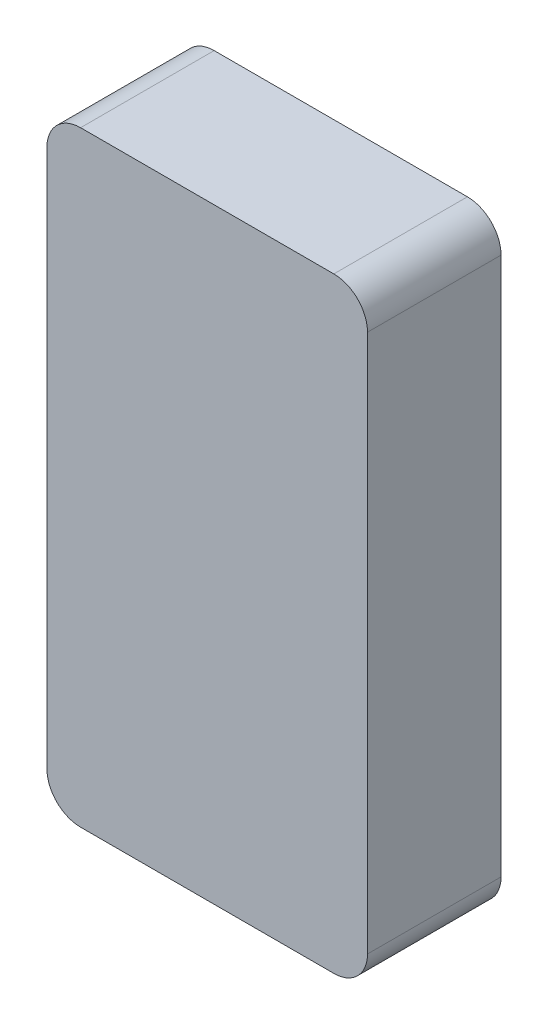
SolidWorks part; units mm, degrees
ref_plane "前基準面" through (0, 0, 0) normal (0, 0, 1) x (1, 0, 0)
ref_plane "上基準面" through (0, 0, 0) normal (0, 1, 0) x (1, 0, 0)
ref_plane "右基準面" through (0, 0, 0) normal (1, 0, 0) x (0, 0, -1)
sketch "Sketch1" plane through (0, 0, 0) normal (0, 0, 1) x (1, 0, 0)
  line L1 (0, 0) -> (4.7625, 0)
  line L2 (0, 0) -> (0, 9)
  line L3 (0, 9) -> (4.7625, 9)
  line L4 (4.7625, 0) -> (4.7625, 9)
  dimension "D1" = 9
  dimension "D2" = 4.7625
extrude "Boss-Extrude1" add sketch "Sketch1" along normal blind 1.9844
fillet "Fillet1" radius 0.5 2 edges at (4.7625, 9, 0.9922) (0, 9, 0.9922)
fillet "Fillet2" radius 0.5 2 edges at (4.7625, 0, 0.9922) (0, 0, 0.9922)
